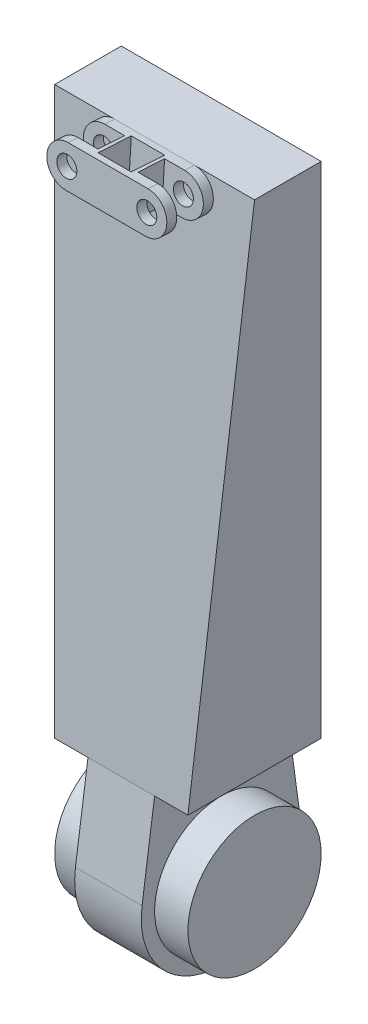
SolidWorks part; units mm, degrees
ref_plane "Alzado" through (0, 0, 0) normal (0, 0, 1) x (1, 0, 0)
ref_plane "Planta" through (0, 0, 0) normal (0, 1, 0) x (1, 0, 0)
ref_plane "Vista lateral" through (0, 0, 0) normal (1, 0, 0) x (0, 0, -1)
ref_plane "Plano1" through (0, 40, 0) normal (0, 1, 0) x (1, 0, 0)
ref_plane "Plano2" through (0, -40, 0) normal (0, 1, 0) x (1, 0, 0)
sketch "Croquis1" plane through (0, -40, 0) normal (0, 1, 0) x (1, 0, 0)
  line L1 (-10, 10) -> (10, 10)
  line L2 (-10, 10) -> (-10, -10)
  line L3 (-10, -10) -> (10, -10)
  line L4 (10, 10) -> (10, -10)
  line L5 (-10, 10) -> (10, -10) construction
  line L6 (-10, -10) -> (10, 10) construction
  point P0 (0, 0)
  dimension "D1" = 20
  dimension "D2" = 20
sketch "Croquis2" plane through (0, 40, 0) normal (0, 1, 0) x (1, 0, 0)
  line L1 (15, -5) -> (-15, -5)
  line L2 (15, -5) -> (15, 5)
  line L3 (15, 5) -> (-15, 5)
  line L4 (-15, -5) -> (-15, 5)
  line L5 (15, -5) -> (-15, 5) construction
  line L6 (15, 5) -> (-15, -5) construction
  point P0 (0, 0)
  dimension "D1" = 30
  dimension "D2" = 10
loft "Recubrir1" add profiles "Croquis2", "Croquis1"
sketch "Croquis3" plane through (0, 0, 0) normal (1, 0, 0) x (0, 0, -1)
  line L0 (0, 0) -> (0, -40) construction
  line L1 (13.2, -40) -> (-13.2, -40) construction
  line L2 (0, -40) -> (0, -55) construction
  line L3 (-10, -40) -> (-11.882, -53.3213)
  line L4 (10, -40) -> (11.6417, -52.0895)
  line L5 (-10, -40) -> (10, -40)
  arc A0 (-11.882, -53.3213) -> (11.6417, -52.0895) centre (0, -55) ccw
  dimension "D2" = 24
  dimension "D1" = 15
extrude "Saliente-Extruir1" add sketch "Croquis3" along normal mid plane 10
sketch "Croquis4" plane through (0, 0, 0) normal (1, 0, 0) x (0, 0, -1)
  circle A0 centre (0, -55) radius 10
  dimension "D1" = 20
extrude "Saliente-Extruir2" add sketch "Croquis4" along normal mid plane 20
sketch "Croquis5" plane through (0, 0.4669, 7.4708) normal (0, 0.0624, 0.9981) x (1, 0, 0)
  line L0 (0, 39.6102) -> (0, 36.6102) construction
  line L1 (15, 39.6102) -> (-15, 39.6102) construction
  line L3 (6, 33.6102) -> (-6, 33.6102)
  line L5 (6, 39.6102) -> (-6, 39.6102)
  line L7 (7.5164, 34.0217) -> (-7.5164, 39.1988) construction
  line L8 (7.5164, 39.1988) -> (-7.5164, 34.0217) construction
  arc A0 (-6, 39.6102) -> (-6, 33.6102) centre (-6, 36.6102) ccw
  arc A1 (6, 33.6102) -> (6, 39.6102) centre (6, 36.6102) ccw
  circle A2 centre (-6, 36.6102) radius 1.5
  circle A3 centre (6, 36.6102) radius 1.5
  point P6 (-9, 36.6102)
  point P9 (9, 36.6102)
  dimension "D3" = 3
  dimension "D4" = 3
  dimension "D1" = 3
  dimension "D2" = 9
  dimension "D5" = 9
extrude "Saliente-Extruir3" add sketch "Croquis5" along normal blind 7
sketch "Croquis6" plane through (0, 39.5331, -2.4708) normal (0, 0.9981, -0.0624) x (1, 0, 0)
  line L0 (6, -14.4854) -> (6, -7.4854) construction
  line L1 (3, -12.9854) -> (9, -12.9854)
  line L2 (3, -12.9854) -> (3, -8.9854)
  line L3 (3, -8.9854) -> (9, -8.9854)
  line L4 (9, -12.9854) -> (9, -8.9854)
  line L5 (3, -12.9854) -> (9, -8.9854) construction
  line L6 (3, -8.9854) -> (9, -12.9854) construction
  line L7 (9, -14.4854) -> (9, -7.4854) construction
  line L8 (-6, -14.4854) -> (-6, -7.4854) construction
  line L9 (-3, -12.9854) -> (-9, -12.9854)
  line L10 (-3, -12.9854) -> (-3, -8.9854)
  line L11 (-3, -8.9854) -> (-9, -8.9854)
  line L12 (-9, -12.9854) -> (-9, -8.9854)
  line L13 (-3, -12.9854) -> (-9, -8.9854) construction
  line L14 (-3, -8.9854) -> (-9, -12.9854) construction
  line L15 (-9, -7.4854) -> (-9, -14.4854) construction
  point P0 (6, -10.9854)
  point P9 (-6, -10.9854)
  dimension "D1" = 4
  dimension "D2" = 4
extrude "Cortar-Extruir1" cut sketch "Croquis6" against normal up to surface (6 mm away) up to face at (0, 34.23, 8.8675)
sketch "Croquis7" plane through (0, 39.5331, -2.4708) normal (0, 0.9981, -0.0624) x (1, 0, 0)
  line L0 (6, -7.4854) -> (-6, -7.4854) construction
  line L1 (-2.5, -13.4854) -> (2.5, -13.4854)
  line L2 (-2.5, -13.4854) -> (-2.5, -8.4854)
  line L3 (-2.5, -8.4854) -> (2.5, -8.4854)
  line L4 (2.5, -13.4854) -> (2.5, -8.4854)
  line L5 (-2.5, -13.4854) -> (2.5, -8.4854) construction
  line L6 (-2.5, -8.4854) -> (2.5, -13.4854) construction
  line L7 (-3, -12.9854) -> (-3, -8.9854) construction
  point P6 (0, -7.4854)
  point P7 (0, -8.4854)
  point P10 (-3, -10.9854)
  point P11 (-2.5, -10.9854)
  dimension "D1" = 5
  dimension "D2" = 5
extrude "Cortar-Extruir2" cut sketch "Croquis7" against normal up to surface (6 mm away) up to face at (0, 34.23, 8.8675)
